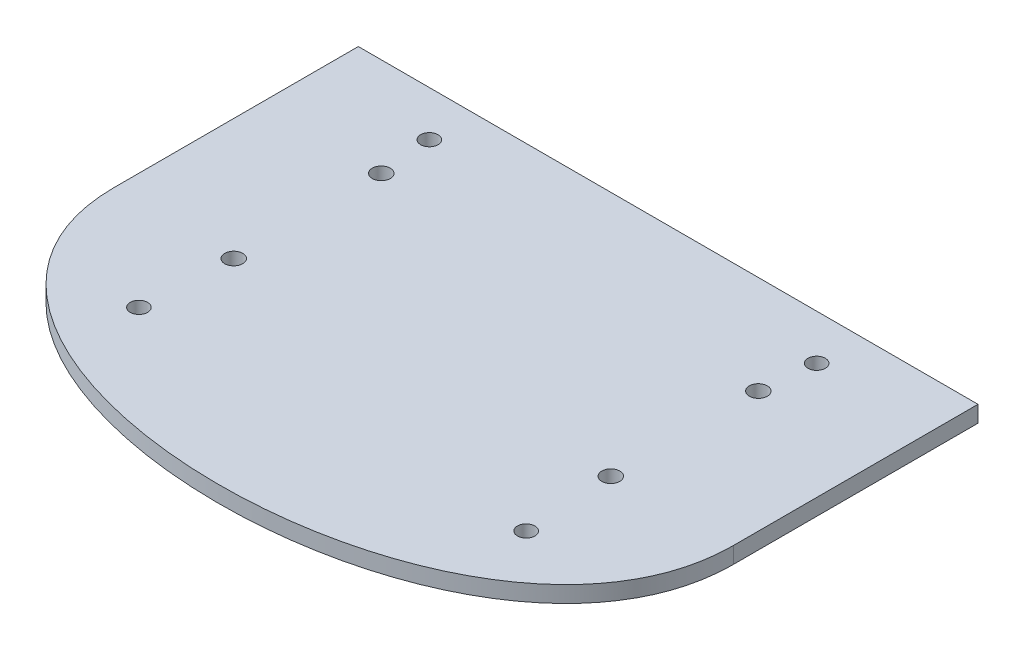
SolidWorks part; units mm, degrees
ref_plane "Front Plane" through (0, 0, 0) normal (0, 0, 1) x (1, 0, 0)
ref_plane "Top Plane" through (0, 0, 0) normal (0, 1, 0) x (1, 0, 0)
ref_plane "Right Plane" through (0, 0, 0) normal (1, 0, 0) x (0, 0, -1)
sketch "Sketch2" plane through (0, 0, 0) normal (0, 1, 0) x (1, 0, 0)
  line L4 (-48.006, -33.6908) -> (-48.006, 91.0268) construction
  line L5 (48.006, -34.798) -> (-48.006, -34.798) construction
  line L6 (48.006, -34.798) -> (48.006, 34.798) construction
  line L7 (48.006, 34.798) -> (-48.006, 34.798)
  line L8 (-48.006, -34.798) -> (-48.006, 34.798) construction
  line L9 (48.006, -34.798) -> (-48.006, 34.798) construction
  line L10 (48.006, 34.798) -> (-48.006, -34.798) construction
  line L11 (48.006, 148.5724) -> (48.006, -105.4276) construction
  line L12 (-48.006, 34.798) -> (-48.006, -3.048)
  line L13 (48.006, 34.798) -> (48.006, -3.048)
  spline S0 degree 3 poles (-48.006, -3.048) (-48.006, -45.3813) (48.006, -45.3813) (48.006, -3.048) knots 0 0 0 0 1 1 1 1
  point P0 (0, 0)
  dimension "D3" = 180
  dimension "D4" = 127
  dimension "D5" = 69.596
  dimension "D1" = 96.012
  dimension "D2" = 180
  dimension "D6" = 127
extrude "Boss-Extrude1" add sketch "Sketch2" along normal blind 2.54
sketch "Sketch3" plane through (0, 2.54, 0) normal (0, 1, 0) x (1, 0, 0)
  line L0 (0, 0) -> (0, 43.6246) construction
  line L10 (48.006, 34.798) -> (-48.006, 34.798) construction
  line L11 (-29.21, 19.558) -> (-29.21, -3.302) construction
  line L12 (29.21, 19.558) -> (29.21, -3.302) construction
  line L13 (-30, 27.798) -> (-30, -17.202) construction
  line L14 (30, 27.798) -> (30, -17.202) construction
  line L15 (0, -34.798) -> (29.21, -34.798) construction
  circle A2 centre (-30, 27.798) radius 1.35
  circle A5 centre (-30, -17.202) radius 1.35
  circle A6 centre (30, -17.202) radius 1.35
  circle A7 centre (30, 27.798) radius 1.35
  circle A10 centre (-29.21, 19.558) radius 1.397
  circle A11 centre (-29.21, -3.302) radius 1.397
  circle A12 centre (29.21, -3.302) radius 1.397
  circle A13 centre (29.21, 19.558) radius 1.397
  spline S0 degree 3 poles (-48.006, -3.048) (-48.006, -45.3813) (48.006, -45.3813) (48.006, -3.048) knots 0 0 0 0 1 1 1 1 construction
  dimension "D5" = 15.24
  dimension "D9" = 2.7
  dimension "D2" = 2.794
  dimension "D3" = 22.86
  dimension "D4" = 29.21
  dimension "D10" = 7
  dimension "D11" = 30
  dimension "D12" = 45
extrude "Cut-Extrude1" cut sketch "Sketch3" against normal through all and the other way through all
